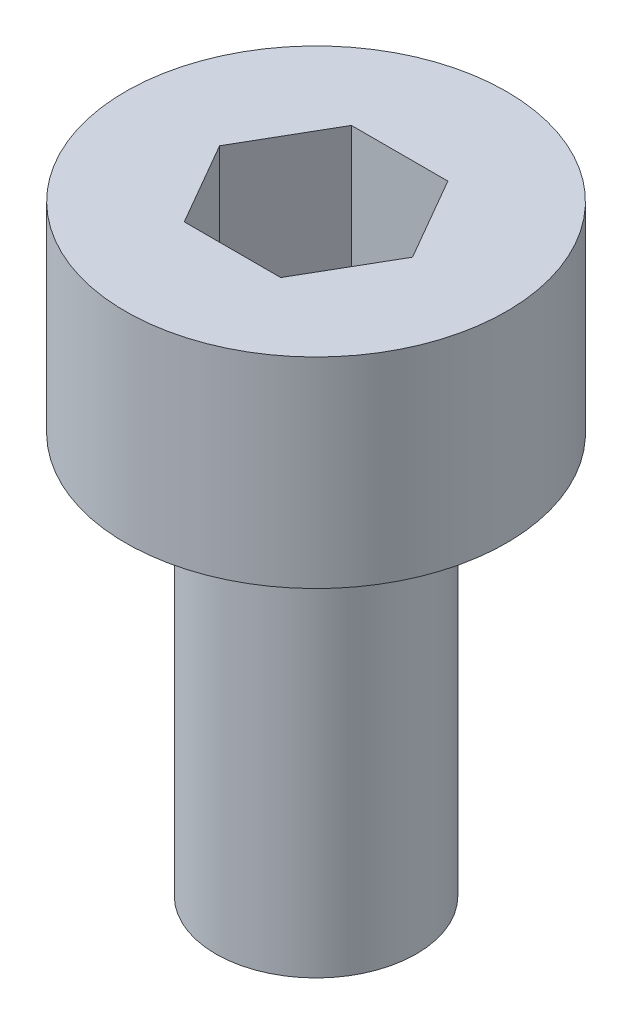
SolidWorks part; units mm, degrees
ref_plane "Front Plane" through (0, 0, 0) normal (0, 0, 1) x (1, 0, 0)
ref_plane "Top Plane" through (0, 0, 0) normal (0, 1, 0) x (1, 0, 0)
ref_plane "Right Plane" through (0, 0, 0) normal (1, 0, 0) x (0, 0, -1)
sketch "Sketch1" plane through (0, 0, 0) normal (1, 0, 0) x (0, 0, -1)
  line L0 (0, -6) -> (1.5, -6)
  line L1 (1.5, -6) -> (1.5, 0)
  line L2 (1.5, 0) -> (2.85, 0)
  line L3 (2.85, 0) -> (2.85, 3)
  line L4 (2.85, 3) -> (0, 3)
  line L5 (0, 3) -> (0, -6)
  line L6 (0, 4) -> (0, 50004) construction
  dimension "D1" = 3
  dimension "D2" = 5.7
  dimension "D3" = 3
  dimension "D4" = 6
revolve "Revolve1" add sketch "Sketch1" angle 360 about L6
sketch "Sketch3" plane through (0, 3, 0) normal (0, 1, 0) x (1, 0, 0)
  line L1 (1.4434, 0) -> (0.7217, 1.25)
  line L2 (0.7217, 1.25) -> (-0.7217, 1.25)
  line L3 (-0.7217, 1.25) -> (-1.4434, 0)
  line L4 (-1.4434, 0) -> (-0.7217, -1.25)
  line L5 (-0.7217, -1.25) -> (0.7217, -1.25)
  line L6 (0.7217, -1.25) -> (1.4434, 0)
  circle A0 centre (0, 0) radius 1.25 construction
  circle A1 centre (0, 0) radius 2.85 construction
  dimension "D1" = 2.5
extrude "Cut-Extrude1" cut sketch "Sketch3" against normal blind 2
